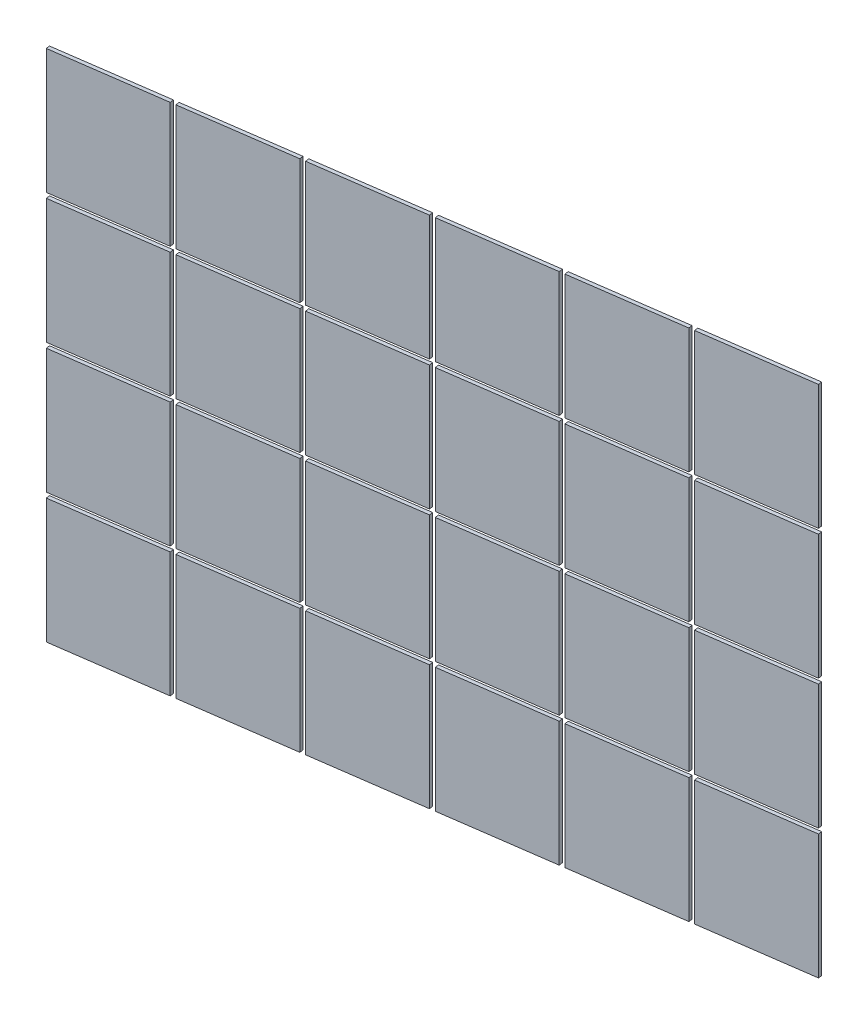
SolidWorks part; units mm, degrees
material "Glass"
ref_plane "Front Plane" through (0, 0, 0) normal (0, 0, 1) x (1, 0, 0)
ref_plane "Top Plane" through (0, 0, 0) normal (0, 1, 0) x (1, 0, 0)
ref_plane "Right Plane" through (0, 0, 0) normal (1, 0, 0) x (0, 0, -1)
sketch "Extrude sketch 1" plane through (0, 0, 0) normal (0, 0, 1) x (1, 0, 0)
  line L0 (-136.8333, -151.5) -> (-136.8333, -78)
  line L1 (-136.8333, -78) -> (-201.5, -78)
  line L2 (-201.5, -78) -> (-201.5, -151.5)
  line L3 (-201.5, -151.5) -> (-136.8333, -151.5)
  dimension "D1" = 64.6667
  dimension "D2" = 73.5
extrude "Extrude 1" add sketch "Extrude sketch 1" along normal blind 2.2 from offset 9.3 separate body
move or copy body "Extrude rotate 1" bodies to move or copy 101 copy no rotation origin (0, 0, 0) rotation axis (0, 1, 0) rotation angle 8
move or copy body "Extrude place 1" bodies to move or copy 102 copy no translate (588.9293, 0, 623.6923) parameters "D1"=588.9293, "D2"=0, "D3"=623.6923
sketch "Extrude sketch 2" plane through (0, 0, 0) normal (0, 0, 1) x (1, 0, 0)
  line L0 (-136.8333, -75) -> (-136.8333, -1.5)
  line L1 (-136.8333, -1.5) -> (-201.5, -1.5)
  line L2 (-201.5, -1.5) -> (-201.5, -75)
  line L3 (-201.5, -75) -> (-136.8333, -75)
  dimension "D1" = 64.6667
  dimension "D2" = 73.5
extrude "Extrude 2" add sketch "Extrude sketch 2" along normal blind 2.2 from offset 9.3 separate body
move or copy body "Extrude rotate 2" bodies to move or copy 104 copy no rotation origin (0, 0, 0) rotation axis (0, 1, 0) rotation angle 8
move or copy body "Extrude place 2" bodies to move or copy 105 copy no translate (588.9293, 0, 623.6923) parameters "D1"=588.9293, "D2"=0, "D3"=623.6923
sketch "Extrude sketch 3" plane through (0, 0, 0) normal (0, 0, 1) x (1, 0, 0)
  line L0 (-136.8333, 1.5) -> (-136.8333, 75)
  line L1 (-136.8333, 75) -> (-201.5, 75)
  line L2 (-201.5, 75) -> (-201.5, 1.5)
  line L3 (-201.5, 1.5) -> (-136.8333, 1.5)
  dimension "D1" = 64.6667
  dimension "D2" = 73.5
extrude "Extrude 3" add sketch "Extrude sketch 3" along normal blind 2.2 from offset 9.3 separate body
move or copy body "Extrude rotate 3" bodies to move or copy 107 copy no rotation origin (0, 0, 0) rotation axis (0, 1, 0) rotation angle 8
move or copy body "Extrude place 3" bodies to move or copy 108 copy no translate (588.9293, 0, 623.6923) parameters "D1"=588.9293, "D2"=0, "D3"=623.6923
sketch "Extrude sketch 4" plane through (0, 0, 0) normal (0, 0, 1) x (1, 0, 0)
  line L0 (-136.8333, 78) -> (-136.8333, 151.5)
  line L1 (-136.8333, 151.5) -> (-201.5, 151.5)
  line L2 (-201.5, 151.5) -> (-201.5, 78)
  line L3 (-201.5, 78) -> (-136.8333, 78)
  dimension "D1" = 64.6667
  dimension "D2" = 73.5
extrude "Extrude 4" add sketch "Extrude sketch 4" along normal blind 2.2 from offset 9.3 separate body
move or copy body "Extrude rotate 4" bodies to move or copy 110 copy no rotation origin (0, 0, 0) rotation axis (0, 1, 0) rotation angle 8
move or copy body "Extrude place 4" bodies to move or copy 111 copy no translate (588.9293, 0, 623.6923) parameters "D1"=588.9293, "D2"=0, "D3"=623.6923
sketch "Extrude sketch 5" plane through (0, 0, 0) normal (0, 0, 1) x (1, 0, 0)
  line L0 (-69.1667, -151.5) -> (-69.1667, -78)
  line L1 (-69.1667, -78) -> (-133.8333, -78)
  line L2 (-133.8333, -78) -> (-133.8333, -151.5)
  line L3 (-133.8333, -151.5) -> (-69.1667, -151.5)
  dimension "D1" = 64.6667
  dimension "D2" = 73.5
extrude "Extrude 5" add sketch "Extrude sketch 5" along normal blind 2.2 from offset 9.3 separate body
move or copy body "Extrude rotate 5" bodies to move or copy 113 copy no rotation origin (0, 0, 0) rotation axis (0, 1, 0) rotation angle 8
move or copy body "Extrude place 5" bodies to move or copy 114 copy no translate (588.9293, 0, 623.6923) parameters "D1"=588.9293, "D2"=0, "D3"=623.6923
sketch "Extrude sketch 6" plane through (0, 0, 0) normal (0, 0, 1) x (1, 0, 0)
  line L0 (-69.1667, -75) -> (-69.1667, -1.5)
  line L1 (-69.1667, -1.5) -> (-133.8333, -1.5)
  line L2 (-133.8333, -1.5) -> (-133.8333, -75)
  line L3 (-133.8333, -75) -> (-69.1667, -75)
  dimension "D1" = 64.6667
  dimension "D2" = 73.5
extrude "Extrude 6" add sketch "Extrude sketch 6" along normal blind 2.2 from offset 9.3 separate body
move or copy body "Extrude rotate 6" bodies to move or copy 116 copy no rotation origin (0, 0, 0) rotation axis (0, 1, 0) rotation angle 8
move or copy body "Extrude place 6" bodies to move or copy 117 copy no translate (588.9293, 0, 623.6923) parameters "D1"=588.9293, "D2"=0, "D3"=623.6923
sketch "Extrude sketch 7" plane through (0, 0, 0) normal (0, 0, 1) x (1, 0, 0)
  line L0 (-69.1667, 1.5) -> (-69.1667, 75)
  line L1 (-69.1667, 75) -> (-133.8333, 75)
  line L2 (-133.8333, 75) -> (-133.8333, 1.5)
  line L3 (-133.8333, 1.5) -> (-69.1667, 1.5)
  dimension "D1" = 64.6667
  dimension "D2" = 73.5
extrude "Extrude 7" add sketch "Extrude sketch 7" along normal blind 2.2 from offset 9.3 separate body
move or copy body "Extrude rotate 7" bodies to move or copy 119 copy no rotation origin (0, 0, 0) rotation axis (0, 1, 0) rotation angle 8
move or copy body "Extrude place 7" bodies to move or copy 120 copy no translate (588.9293, 0, 623.6923) parameters "D1"=588.9293, "D2"=0, "D3"=623.6923
sketch "Extrude sketch 8" plane through (0, 0, 0) normal (0, 0, 1) x (1, 0, 0)
  line L0 (-69.1667, 78) -> (-69.1667, 151.5)
  line L1 (-69.1667, 151.5) -> (-133.8333, 151.5)
  line L2 (-133.8333, 151.5) -> (-133.8333, 78)
  line L3 (-133.8333, 78) -> (-69.1667, 78)
  dimension "D1" = 64.6667
  dimension "D2" = 73.5
extrude "Extrude 8" add sketch "Extrude sketch 8" along normal blind 2.2 from offset 9.3 separate body
move or copy body "Extrude rotate 8" bodies to move or copy 122 copy no rotation origin (0, 0, 0) rotation axis (0, 1, 0) rotation angle 8
move or copy body "Extrude place 8" bodies to move or copy 123 copy no translate (588.9293, 0, 623.6923) parameters "D1"=588.9293, "D2"=0, "D3"=623.6923
sketch "Extrude sketch 9" plane through (0, 0, 0) normal (0, 0, 1) x (1, 0, 0)
  line L0 (-1.5, -151.5) -> (-1.5, -78)
  line L1 (-1.5, -78) -> (-66.1667, -78)
  line L2 (-66.1667, -78) -> (-66.1667, -151.5)
  line L3 (-66.1667, -151.5) -> (-1.5, -151.5)
  dimension "D1" = 64.6667
  dimension "D2" = 73.5
extrude "Extrude 9" add sketch "Extrude sketch 9" along normal blind 2.2 from offset 9.3 separate body
move or copy body "Extrude rotate 9" bodies to move or copy 125 copy no rotation origin (0, 0, 0) rotation axis (0, 1, 0) rotation angle 8
move or copy body "Extrude place 9" bodies to move or copy 126 copy no translate (588.9293, 0, 623.6923) parameters "D1"=588.9293, "D2"=0, "D3"=623.6923
sketch "Extrude sketch 10" plane through (0, 0, 0) normal (0, 0, 1) x (1, 0, 0)
  line L0 (-1.5, -75) -> (-1.5, -1.5)
  line L1 (-1.5, -1.5) -> (-66.1667, -1.5)
  line L2 (-66.1667, -1.5) -> (-66.1667, -75)
  line L3 (-66.1667, -75) -> (-1.5, -75)
  dimension "D1" = 64.6667
  dimension "D2" = 73.5
extrude "Extrude 10" add sketch "Extrude sketch 10" along normal blind 2.2 from offset 9.3 separate body
move or copy body "Extrude rotate 10" bodies to move or copy 128 copy no rotation origin (0, 0, 0) rotation axis (0, 1, 0) rotation angle 8
move or copy body "Extrude place 10" bodies to move or copy 129 copy no translate (588.9293, 0, 623.6923) parameters "D1"=588.9293, "D2"=0, "D3"=623.6923
sketch "Extrude sketch 11" plane through (0, 0, 0) normal (0, 0, 1) x (1, 0, 0)
  line L0 (-1.5, 1.5) -> (-1.5, 75)
  line L1 (-1.5, 75) -> (-66.1667, 75)
  line L2 (-66.1667, 75) -> (-66.1667, 1.5)
  line L3 (-66.1667, 1.5) -> (-1.5, 1.5)
  dimension "D1" = 64.6667
  dimension "D2" = 73.5
extrude "Extrude 11" add sketch "Extrude sketch 11" along normal blind 2.2 from offset 9.3 separate body
move or copy body "Extrude rotate 11" bodies to move or copy 131 copy no rotation origin (0, 0, 0) rotation axis (0, 1, 0) rotation angle 8
move or copy body "Extrude place 11" bodies to move or copy 132 copy no translate (588.9293, 0, 623.6923) parameters "D1"=588.9293, "D2"=0, "D3"=623.6923
sketch "Extrude sketch 12" plane through (0, 0, 0) normal (0, 0, 1) x (1, 0, 0)
  line L0 (-1.5, 78) -> (-1.5, 151.5)
  line L1 (-1.5, 151.5) -> (-66.1667, 151.5)
  line L2 (-66.1667, 151.5) -> (-66.1667, 78)
  line L3 (-66.1667, 78) -> (-1.5, 78)
  dimension "D1" = 64.6667
  dimension "D2" = 73.5
extrude "Extrude 12" add sketch "Extrude sketch 12" along normal blind 2.2 from offset 9.3 separate body
move or copy body "Extrude rotate 12" bodies to move or copy 134 copy no rotation origin (0, 0, 0) rotation axis (0, 1, 0) rotation angle 8
move or copy body "Extrude place 12" bodies to move or copy 135 copy no translate (588.9293, 0, 623.6923) parameters "D1"=588.9293, "D2"=0, "D3"=623.6923
sketch "Extrude sketch 13" plane through (0, 0, 0) normal (0, 0, 1) x (1, 0, 0)
  line L0 (66.1667, -151.5) -> (66.1667, -78)
  line L1 (66.1667, -78) -> (1.5, -78)
  line L2 (1.5, -78) -> (1.5, -151.5)
  line L3 (1.5, -151.5) -> (66.1667, -151.5)
  dimension "D1" = 64.6667
  dimension "D2" = 73.5
extrude "Extrude 13" add sketch "Extrude sketch 13" along normal blind 2.2 from offset 9.3 separate body
move or copy body "Extrude rotate 13" bodies to move or copy 137 copy no rotation origin (0, 0, 0) rotation axis (0, 1, 0) rotation angle 8
move or copy body "Extrude place 13" bodies to move or copy 138 copy no translate (588.9293, 0, 623.6923) parameters "D1"=588.9293, "D2"=0, "D3"=623.6923
sketch "Extrude sketch 14" plane through (0, 0, 0) normal (0, 0, 1) x (1, 0, 0)
  line L0 (66.1667, -75) -> (66.1667, -1.5)
  line L1 (66.1667, -1.5) -> (1.5, -1.5)
  line L2 (1.5, -1.5) -> (1.5, -75)
  line L3 (1.5, -75) -> (66.1667, -75)
  dimension "D1" = 64.6667
  dimension "D2" = 73.5
extrude "Extrude 14" add sketch "Extrude sketch 14" along normal blind 2.2 from offset 9.3 separate body
move or copy body "Extrude rotate 14" bodies to move or copy 140 copy no rotation origin (0, 0, 0) rotation axis (0, 1, 0) rotation angle 8
move or copy body "Extrude place 14" bodies to move or copy 141 copy no translate (588.9293, 0, 623.6923) parameters "D1"=588.9293, "D2"=0, "D3"=623.6923
sketch "Extrude sketch 15" plane through (0, 0, 0) normal (0, 0, 1) x (1, 0, 0)
  line L0 (66.1667, 1.5) -> (66.1667, 75)
  line L1 (66.1667, 75) -> (1.5, 75)
  line L2 (1.5, 75) -> (1.5, 1.5)
  line L3 (1.5, 1.5) -> (66.1667, 1.5)
  dimension "D1" = 64.6667
  dimension "D2" = 73.5
extrude "Extrude 15" add sketch "Extrude sketch 15" along normal blind 2.2 from offset 9.3 separate body
move or copy body "Extrude rotate 15" bodies to move or copy 143 copy no rotation origin (0, 0, 0) rotation axis (0, 1, 0) rotation angle 8
move or copy body "Extrude place 15" bodies to move or copy 144 copy no translate (588.9293, 0, 623.6923) parameters "D1"=588.9293, "D2"=0, "D3"=623.6923
sketch "Extrude sketch 16" plane through (0, 0, 0) normal (0, 0, 1) x (1, 0, 0)
  line L0 (66.1667, 78) -> (66.1667, 151.5)
  line L1 (66.1667, 151.5) -> (1.5, 151.5)
  line L2 (1.5, 151.5) -> (1.5, 78)
  line L3 (1.5, 78) -> (66.1667, 78)
  dimension "D1" = 64.6667
  dimension "D2" = 73.5
extrude "Extrude 16" add sketch "Extrude sketch 16" along normal blind 2.2 from offset 9.3 separate body
move or copy body "Extrude rotate 16" bodies to move or copy 146 copy no rotation origin (0, 0, 0) rotation axis (0, 1, 0) rotation angle 8
move or copy body "Extrude place 16" bodies to move or copy 147 copy no translate (588.9293, 0, 623.6923) parameters "D1"=588.9293, "D2"=0, "D3"=623.6923
sketch "Extrude sketch 17" plane through (0, 0, 0) normal (0, 0, 1) x (1, 0, 0)
  line L0 (133.8333, -151.5) -> (133.8333, -78)
  line L1 (133.8333, -78) -> (69.1667, -78)
  line L2 (69.1667, -78) -> (69.1667, -151.5)
  line L3 (69.1667, -151.5) -> (133.8333, -151.5)
  dimension "D1" = 64.6667
  dimension "D2" = 73.5
extrude "Extrude 17" add sketch "Extrude sketch 17" along normal blind 2.2 from offset 9.3 separate body
move or copy body "Extrude rotate 17" bodies to move or copy 149 copy no rotation origin (0, 0, 0) rotation axis (0, 1, 0) rotation angle 8
move or copy body "Extrude place 17" bodies to move or copy 150 copy no translate (588.9293, 0, 623.6923) parameters "D1"=588.9293, "D2"=0, "D3"=623.6923
sketch "Extrude sketch 18" plane through (0, 0, 0) normal (0, 0, 1) x (1, 0, 0)
  line L0 (133.8333, -75) -> (133.8333, -1.5)
  line L1 (133.8333, -1.5) -> (69.1667, -1.5)
  line L2 (69.1667, -1.5) -> (69.1667, -75)
  line L3 (69.1667, -75) -> (133.8333, -75)
  dimension "D1" = 64.6667
  dimension "D2" = 73.5
extrude "Extrude 18" add sketch "Extrude sketch 18" along normal blind 2.2 from offset 9.3 separate body
move or copy body "Extrude rotate 18" bodies to move or copy 152 copy no rotation origin (0, 0, 0) rotation axis (0, 1, 0) rotation angle 8
move or copy body "Extrude place 18" bodies to move or copy 153 copy no translate (588.9293, 0, 623.6923) parameters "D1"=588.9293, "D2"=0, "D3"=623.6923
sketch "Extrude sketch 19" plane through (0, 0, 0) normal (0, 0, 1) x (1, 0, 0)
  line L0 (133.8333, 1.5) -> (133.8333, 75)
  line L1 (133.8333, 75) -> (69.1667, 75)
  line L2 (69.1667, 75) -> (69.1667, 1.5)
  line L3 (69.1667, 1.5) -> (133.8333, 1.5)
  dimension "D1" = 64.6667
  dimension "D2" = 73.5
extrude "Extrude 19" add sketch "Extrude sketch 19" along normal blind 2.2 from offset 9.3 separate body
move or copy body "Extrude rotate 19" bodies to move or copy 155 copy no rotation origin (0, 0, 0) rotation axis (0, 1, 0) rotation angle 8
move or copy body "Extrude place 19" bodies to move or copy 156 copy no translate (588.9293, 0, 623.6923) parameters "D1"=588.9293, "D2"=0, "D3"=623.6923
sketch "Extrude sketch 20" plane through (0, 0, 0) normal (0, 0, 1) x (1, 0, 0)
  line L0 (133.8333, 78) -> (133.8333, 151.5)
  line L1 (133.8333, 151.5) -> (69.1667, 151.5)
  line L2 (69.1667, 151.5) -> (69.1667, 78)
  line L3 (69.1667, 78) -> (133.8333, 78)
  dimension "D1" = 64.6667
  dimension "D2" = 73.5
extrude "Extrude 20" add sketch "Extrude sketch 20" along normal blind 2.2 from offset 9.3 separate body
move or copy body "Extrude rotate 20" bodies to move or copy 158 copy no rotation origin (0, 0, 0) rotation axis (0, 1, 0) rotation angle 8
move or copy body "Extrude place 20" bodies to move or copy 159 copy no translate (588.9293, 0, 623.6923) parameters "D1"=588.9293, "D2"=0, "D3"=623.6923
sketch "Extrude sketch 21" plane through (0, 0, 0) normal (0, 0, 1) x (1, 0, 0)
  line L0 (201.5, -151.5) -> (201.5, -78)
  line L1 (201.5, -78) -> (136.8333, -78)
  line L2 (136.8333, -78) -> (136.8333, -151.5)
  line L3 (136.8333, -151.5) -> (201.5, -151.5)
  dimension "D1" = 64.6667
  dimension "D2" = 73.5
extrude "Extrude 21" add sketch "Extrude sketch 21" along normal blind 2.2 from offset 9.3 separate body
move or copy body "Extrude rotate 21" bodies to move or copy 161 copy no rotation origin (0, 0, 0) rotation axis (0, 1, 0) rotation angle 8
move or copy body "Extrude place 21" bodies to move or copy 162 copy no translate (588.9293, 0, 623.6923) parameters "D1"=588.9293, "D2"=0, "D3"=623.6923
sketch "Extrude sketch 22" plane through (0, 0, 0) normal (0, 0, 1) x (1, 0, 0)
  line L0 (201.5, -75) -> (201.5, -1.5)
  line L1 (201.5, -1.5) -> (136.8333, -1.5)
  line L2 (136.8333, -1.5) -> (136.8333, -75)
  line L3 (136.8333, -75) -> (201.5, -75)
  dimension "D1" = 64.6667
  dimension "D2" = 73.5
extrude "Extrude 22" add sketch "Extrude sketch 22" along normal blind 2.2 from offset 9.3 separate body
move or copy body "Extrude rotate 22" bodies to move or copy 164 copy no rotation origin (0, 0, 0) rotation axis (0, 1, 0) rotation angle 8
move or copy body "Extrude place 22" bodies to move or copy 165 copy no translate (588.9293, 0, 623.6923) parameters "D1"=588.9293, "D2"=0, "D3"=623.6923
sketch "Extrude sketch 23" plane through (0, 0, 0) normal (0, 0, 1) x (1, 0, 0)
  line L0 (201.5, 1.5) -> (201.5, 75)
  line L1 (201.5, 75) -> (136.8333, 75)
  line L2 (136.8333, 75) -> (136.8333, 1.5)
  line L3 (136.8333, 1.5) -> (201.5, 1.5)
  dimension "D1" = 64.6667
  dimension "D2" = 73.5
extrude "Extrude 23" add sketch "Extrude sketch 23" along normal blind 2.2 from offset 9.3 separate body
move or copy body "Extrude rotate 23" bodies to move or copy 167 copy no rotation origin (0, 0, 0) rotation axis (0, 1, 0) rotation angle 8
move or copy body "Extrude place 23" bodies to move or copy 168 copy no translate (588.9293, 0, 623.6923) parameters "D1"=588.9293, "D2"=0, "D3"=623.6923
sketch "Extrude sketch 24" plane through (0, 0, 0) normal (0, 0, 1) x (1, 0, 0)
  line L0 (201.5, 78) -> (201.5, 151.5)
  line L1 (201.5, 151.5) -> (136.8333, 151.5)
  line L2 (136.8333, 151.5) -> (136.8333, 78)
  line L3 (136.8333, 78) -> (201.5, 78)
  dimension "D1" = 64.6667
  dimension "D2" = 73.5
extrude "Extrude 24" add sketch "Extrude sketch 24" along normal blind 2.2 from offset 9.3 separate body
move or copy body "Extrude rotate 24" bodies to move or copy 170 copy no rotation origin (0, 0, 0) rotation axis (0, 1, 0) rotation angle 8
move or copy body "Extrude place 24" bodies to move or copy 171 copy no translate (588.9293, 0, 623.6923) parameters "D1"=588.9293, "D2"=0, "D3"=623.6923
